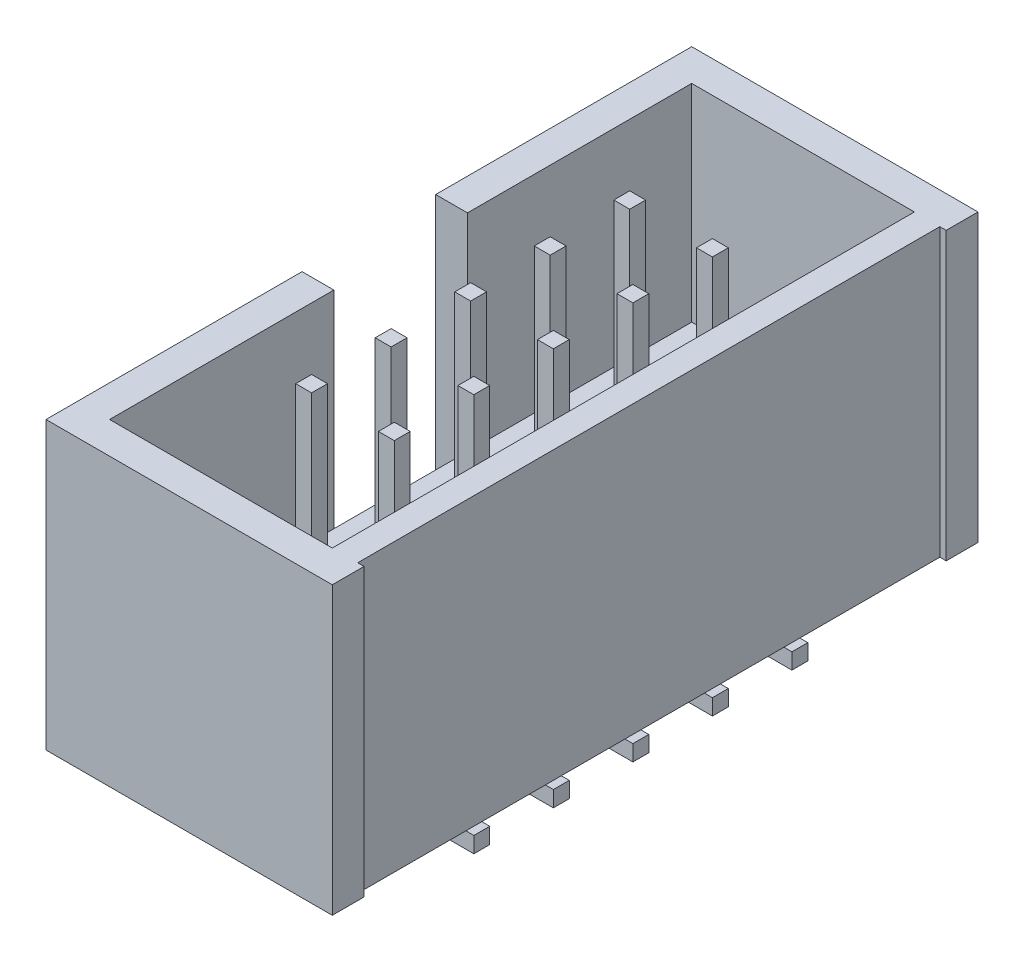
SolidWorks part; units mm, degrees
ref_plane "Alzado" through (0, 0, 0) normal (0, 0, 1) x (1, 0, 0)
ref_plane "Planta" through (0, 0, 0) normal (0, 1, 0) x (1, 0, 0)
ref_plane "Vista lateral" through (0, 0, 0) normal (1, 0, 0) x (0, 0, -1)
sketch "Croquis1" plane through (0, 0, 0) normal (0, 1, 0) x (1, 0, 0)
  line L1 (0, 0) -> (9, 0)
  line L2 (0, 0) -> (0, 20.3)
  line L3 (0, 20.3) -> (9, 20.3)
  line L4 (9, 0) -> (9, 20.3)
  dimension "D1" = 9
  dimension "D2" = 20.3
extrude "Saliente-Extruir1" add sketch "Croquis1" along normal blind 9
sketch "Croquis2" plane through (0, 9, 0) normal (0, 1, 0) x (1, 0, 0)
  line L8 (1, 19.3) -> (1, 1)
  line L9 (1, 1) -> (8, 1)
  line L10 (8, 1) -> (8, 19.3)
  line L11 (8, 19.3) -> (1, 19.3)
  line L12 (1, 19.3) -> (1, 1)
  line L13 (1, 1) -> (8, 1)
  line L14 (8, 1) -> (8, 19.3)
  line L15 (8, 19.3) -> (1, 19.3)
  dimension "D1" = 1
extrude "Cortar-Extruir1" cut sketch "Croquis2" against normal blind 6.5
sketch "Croquis3" plane through (9, 0, 0) normal (1, 0, 0) x (0, 0, -1)
  line L0 (0, 9) -> (20.3, 9) construction
  line L1 (1, 9) -> (19.3, 9)
  line L2 (1, 9) -> (1, 0)
  line L3 (1, 0) -> (19.3, 0)
  line L4 (19.3, 9) -> (19.3, 0)
  line L5 (0, 0) -> (20.3, 0) construction
  line L6 (0, 9) -> (0, 0) construction
  line L7 (20.3, 9) -> (20.3, 0) construction
  dimension "D1" = 1
  dimension "D2" = 1
extrude "Cortar-Extruir2" cut sketch "Croquis3" against normal blind 0.2
sketch "Croquis4" plane through (0, 0, 0) normal (-1, 0, 0) x (0, 0, 1)
  line L0 (-10.15, 9) -> (-10.15, 0) construction
  line L1 (-20.3, 9) -> (0, 9) construction
  line L2 (-20.3, 0) -> (0, 0) construction
  line L4 (-12.25, 9) -> (-8.05, 9)
  line L5 (-12.25, 9) -> (-12.25, 1.3)
  line L6 (-12.25, 1.3) -> (-8.05, 1.3)
  line L7 (-8.05, 9) -> (-8.05, 1.3)
  point P10 (-10.15, 9)
  dimension "D1" = 4.2
  dimension "D2" = 1.3
extrude "Cortar-Extruir3" cut sketch "Croquis4" against normal blind 1
sketch "Croquis5" plane through (0, 9, 0) normal (0, 1, 0) x (1, 0, 0)
  line L0 (4.5, 0) -> (4.5, 20.3) construction
  line L1 (0, 0) -> (9, 0) construction
  line L2 (9, 20.3) -> (0, 20.3) construction
  line L3 (3.2, 0) -> (3.2, 20.3) construction
  line L4 (5.55, 15.4) -> (6.05, 15.4)
  line L5 (2.95, 14.9) -> (3.45, 14.9)
  line L6 (2.95, 14.9) -> (2.95, 15.4)
  line L7 (2.95, 15.4) -> (3.45, 15.4)
  line L8 (3.45, 14.9) -> (3.45, 15.4)
  line L9 (2.95, 14.9) -> (3.45, 15.4) construction
  line L10 (2.95, 15.4) -> (3.45, 14.9) construction
  line L11 (5.55, 14.9) -> (5.55, 15.4)
  line L12 (5.55, 14.9) -> (6.05, 14.9)
  line L13 (6.05, 14.9) -> (6.05, 15.4)
  line L14 (5.55, 12.9) -> (6.05, 12.9)
  line L15 (5.55, 12.4) -> (5.55, 12.9)
  line L16 (5.55, 12.4) -> (6.05, 12.4)
  line L17 (6.05, 12.4) -> (6.05, 12.9)
  line L18 (5.55, 10.4) -> (6.05, 10.4)
  line L19 (5.55, 9.9) -> (5.55, 10.4)
  line L20 (5.55, 9.9) -> (6.05, 9.9)
  line L21 (6.05, 9.9) -> (6.05, 10.4)
  line L22 (5.55, 7.9) -> (6.05, 7.9)
  line L23 (5.55, 7.4) -> (5.55, 7.9)
  line L24 (5.55, 7.4) -> (6.05, 7.4)
  line L25 (6.05, 7.4) -> (6.05, 7.9)
  line L26 (5.55, 5.4) -> (6.05, 5.4)
  line L27 (5.55, 4.9) -> (5.55, 5.4)
  line L28 (5.55, 4.9) -> (6.05, 4.9)
  line L29 (6.05, 4.9) -> (6.05, 5.4)
  line L30 (2.95, 12.9) -> (3.45, 12.9)
  line L31 (2.95, 12.4) -> (2.95, 12.9)
  line L32 (2.95, 12.4) -> (3.45, 12.4)
  line L33 (3.45, 12.4) -> (3.45, 12.9)
  line L34 (2.95, 10.4) -> (3.45, 10.4)
  line L35 (2.95, 9.9) -> (2.95, 10.4)
  line L36 (2.95, 9.9) -> (3.45, 9.9)
  line L37 (3.45, 9.9) -> (3.45, 10.4)
  line L38 (2.95, 7.9) -> (3.45, 7.9)
  line L39 (2.95, 7.4) -> (2.95, 7.9)
  line L40 (2.95, 7.4) -> (3.45, 7.4)
  line L41 (3.45, 7.4) -> (3.45, 7.9)
  line L42 (2.95, 5.4) -> (3.45, 5.4)
  line L43 (2.95, 4.9) -> (2.95, 5.4)
  line L44 (2.95, 4.9) -> (3.45, 4.9)
  line L45 (3.45, 4.9) -> (3.45, 5.4)
  point P8 (3.2, 15.15)
  point P13 (4.5, 10.15)
  dimension "D1" = 1.3
  dimension "D2" = 0.5
  dimension "D3" = 4.75
  dimension "D4" = 2
  dimension "D5" = 5
extrude "Saliente-Extruir2" add sketch "Croquis5" against normal blind 10
sketch "Croquis6" plane through (2.95, 0, 0) normal (-1, 0, 0) x (0, 0, 1)
  line L0 (-5.4, -1) -> (-5.4, 0) construction
  line L1 (-4.9, -1) -> (-5.4, -1)
  line L2 (-4.9, -1) -> (-4.9, -0.5)
  line L3 (-4.9, -0.5) -> (-5.4, -0.5)
  line L4 (-5.4, -1) -> (-5.4, -0.5)
  line L5 (-7.4, -1) -> (-7.9, -1)
  line L6 (-7.4, -1) -> (-7.4, -0.5)
  line L7 (-7.4, -0.5) -> (-7.9, -0.5)
  line L8 (-7.9, -1) -> (-7.9, -0.5)
  line L9 (-9.9, -1) -> (-10.4, -1)
  line L10 (-9.9, -1) -> (-9.9, -0.5)
  line L11 (-9.9, -0.5) -> (-10.4, -0.5)
  line L12 (-10.4, -1) -> (-10.4, -0.5)
  line L13 (-12.4, -1) -> (-12.9, -1)
  line L14 (-12.4, -1) -> (-12.4, -0.5)
  line L15 (-12.4, -0.5) -> (-12.9, -0.5)
  line L16 (-12.9, -1) -> (-12.9, -0.5)
  line L17 (-14.9, -1) -> (-15.4, -1)
  line L18 (-14.9, -1) -> (-14.9, -0.5)
  line L19 (-14.9, -0.5) -> (-15.4, -0.5)
  line L20 (-15.4, -1) -> (-15.4, -0.5)
  dimension "D1" = 5
extrude "Saliente-Extruir3" add sketch "Croquis6" along normal blind 2.5
ref_plane "Plano1" through (4.5, 0, 0) normal (1, 0, 0) x (0, 0, -1)
mirror "Simetría1" about plane through (4.5, 0, 0) normal (1, 0, 0) of "Saliente-Extruir3"
